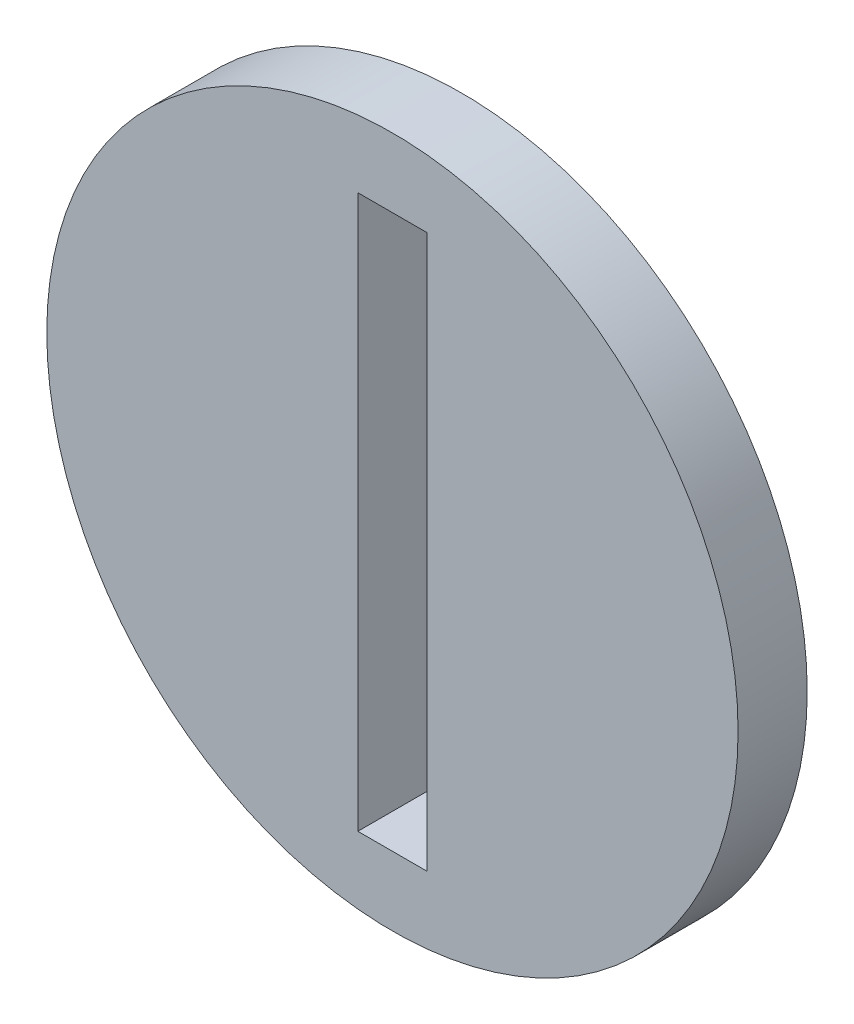
SolidWorks part; units mm, degrees
other "Markup1"
sketch "Sketch2" plane through (15.875, 15.875, 3.175) normal (0.4, 0.515, 0.7581) x (0.8844, 0, -0.4667)
ref_plane "Front Plane" through (0, 0, 0) normal (0, 0, 1) x (1, 0, 0)
ref_plane "Top Plane" through (0, 0, 0) normal (0, 1, 0) x (1, 0, 0)
ref_plane "Right Plane" through (0, 0, 0) normal (1, 0, 0) x (0, 0, -1)
sketch "Sketch1" plane through (0, 0, 0) normal (0, 0, 1) x (1, 0, 0)
  line L1 (-1.5875, 12.7) -> (1.5875, 12.7)
  line L3 (-1.5875, -12.7) -> (1.5875, -12.7)
  line L4 (1.5875, 12.7) -> (1.5875, -12.7)
  line L5 (-1.5875, 12.7) -> (-1.5875, -12.7)
  circle A0 centre (0, 0) radius 15.875
  point P6 (0, 0)
extrude "Boss-Extrude1" add sketch "Sketch1" along normal blind 3.175
